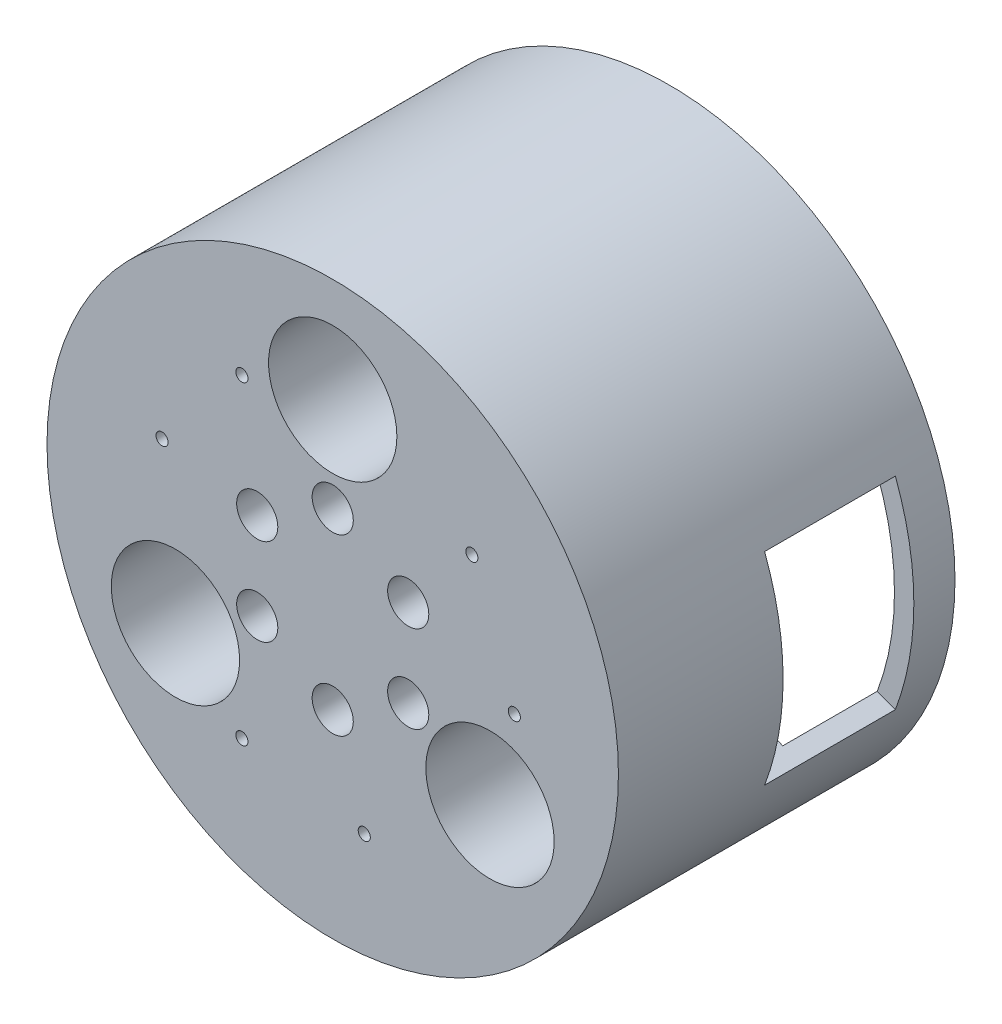
SolidWorks part; units mm, degrees
ref_plane "前视基准面" through (0, 0, 0) normal (0, 0, 1) x (1, 0, 0)
ref_plane "上视基准面" through (0, 0, 0) normal (0, 1, 0) x (1, 0, 0)
ref_plane "右视基准面" through (0, 0, 0) normal (1, 0, 0) x (0, 0, -1)
other "Configuration Table"
sketch "草图1" plane through (0, 0, 0) normal (0, 0, 1) x (1, 0, 0)
  circle A0 centre (0, 0) radius 59
extrude "01_BODY_D118" add sketch "草图1" along normal blind 69.5
sketch "草图2" plane through (0, 0, 0) normal (0, 0, 1) x (1, 0, 0)
  circle A0 centre (0, 0) radius 55
extrude "02_BORE_D110" cut sketch "草图2" along normal blind 28
ref_plane "Plane_P28" through (0, 0, 28) normal (0, 0, 1) x (1, 0, 0)
sketch "草图3" plane through (0, 0, 28) normal (0, 0, 1) x (1, 0, 0)
  circle A0 centre (0, 0) radius 54
extrude "03_BORE_D108" cut sketch "草图3" along normal blind 12
ref_plane "Plane_End" through (0, 0, 69.5) normal (0, 0, 1) x (1, 0, 0)
sketch "草图4" plane through (0, 0, 69.5) normal (0, 0, 1) x (1, 0, 0)
  circle A0 centre (15.5885, 9) radius 4.25
  circle A1 centre (0, 18) radius 4.25
  circle A2 centre (-15.5885, 9) radius 4.25
  circle A3 centre (-15.5885, -9) radius 4.25
  circle A4 centre (0, -18) radius 4.25
  circle A5 centre (15.5885, -9) radius 4.25
extrude "04_HOLES_6_D8.5" cut sketch "草图4" against normal blind 24
sketch "草图5" plane through (0, 0, 69.5) normal (0, 0, 1) x (1, 0, 0)
  circle A0 centre (0, 37.5) radius 13.25
  circle A1 centre (-32.476, -18.75) radius 13.25
  circle A2 centre (32.476, -18.75) radius 13.25
extrude "05_LOBES_3_D26.5" cut sketch "草图5" against normal blind 19.5
ref_plane "Plane_LobeBottom" through (0, 0, 50) normal (0, 0, 1) x (1, 0, 0)
sketch "草图6" plane through (0, 0, 50) normal (0, 0, 1) x (1, 0, 0)
  circle A0 centre (0, 37.5) radius 9
  circle A1 centre (-32.476, -18.75) radius 9
  circle A2 centre (32.476, -18.75) radius 9
extrude "06_THRU_3_D18" cut sketch "草图6" against normal blind 10
ref_plane "Plane_Win" through (0, 0, 8.5) normal (0, 0, 1) x (1, 0, 0)
sketch "草图7" plane through (0, 0, 8.5) normal (0, 0, 1) x (1, 0, 0)
  line L0 (55.1799, 20.885) -> (50.5036, 19.115)
  line L1 (50.5036, -19.115) -> (55.1799, -20.885)
  arc A0 (55.1799, -20.885) -> (55.1799, 20.885) centre (0, 0) ccw
  arc A1 (50.5036, 19.115) -> (50.5036, -19.115) centre (0, 0) cw
extrude "07_WINDOW_27X40" cut sketch "草图7" along normal blind 27
sketch "草图8" plane through (0, 0, 69.5) normal (0, 0, 1) x (1, 0, 0)
  circle A0 centre (-18.75, 32.476) radius 1.25
  circle A1 centre (-35.2385, 12.8258) radius 1.25
  circle A2 centre (-35.2385, -12.8258) radius 1.25
  circle A3 centre (-18.75, -32.476) radius 1.25
  circle A4 centre (6.5118, -36.9303) radius 1.25
  circle A5 centre (28.7267, -24.1045) radius 1.25
  circle A6 centre (37.5, 0) radius 1.25
  circle A7 centre (28.7267, 24.1045) radius 1.25
  circle A8 centre (6.5118, 36.9303) radius 1.25
extrude "08_TAP_9_M3" cut sketch "草图8" against normal blind 6
